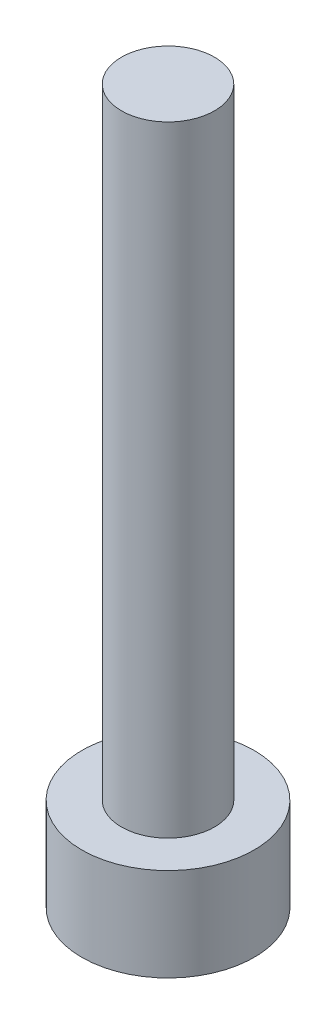
SolidWorks part; units mm, degrees
ref_plane "Front Plane" through (0, 0, 0) normal (0, 0, 1) x (1, 0, 0)
ref_plane "Top Plane" through (0, 0, 0) normal (0, 1, 0) x (1, 0, 0)
ref_plane "Right Plane" through (0, 0, 0) normal (1, 0, 0) x (0, 0, -1)
sketch "Sketch1" plane through (0, 0, 0) normal (0, 1, 0) x (1, 0, 0)
  circle A0 centre (0, 0) radius 2.78
  dimension "D1" = 5.56
extrude "Boss-Extrude1" add sketch "Sketch1" along normal blind 3
sketch "Sketch2" plane through (0, 3, 0) normal (0, 1, 0) x (1, 0, 0)
  circle A0 centre (0, 0) radius 1.5
  dimension "D1" = 3
extrude "Boss-Extrude2" add sketch "Sketch2" along normal blind 20
